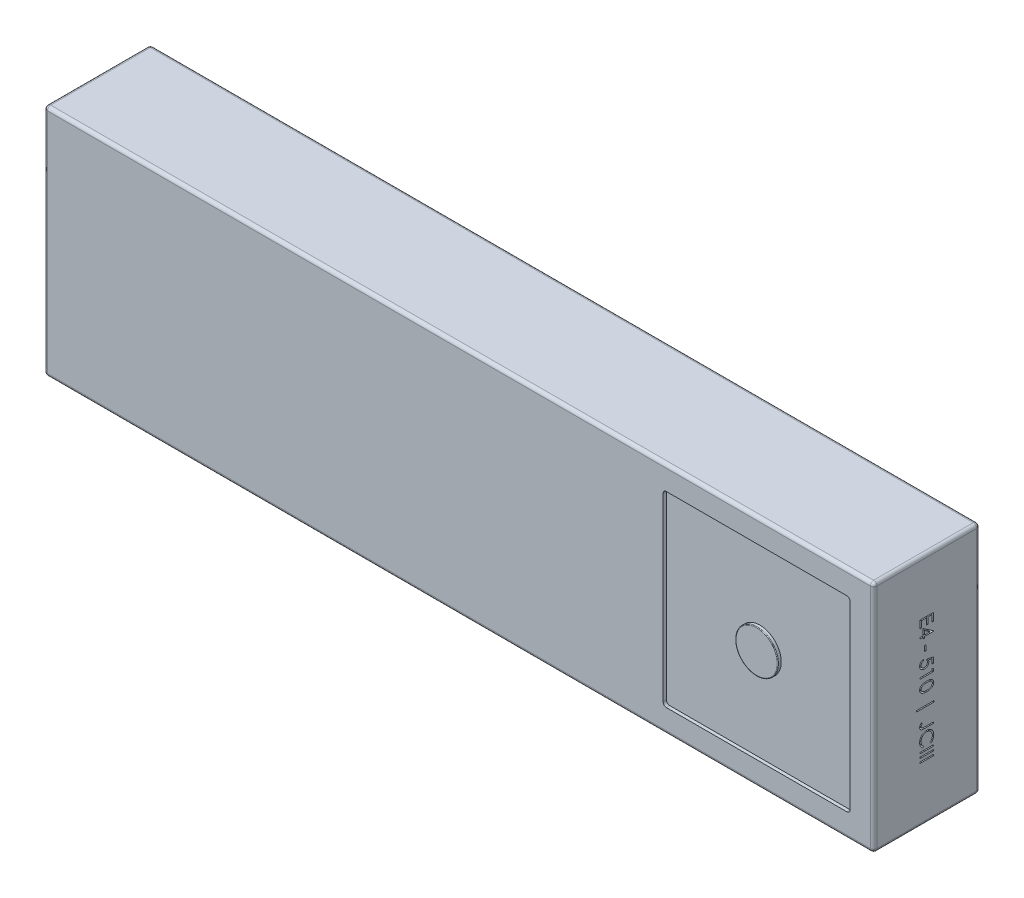
SolidWorks part; units mm, degrees
ref_plane "Front Plane" through (0, 0, 0) normal (0, 0, 1) x (1, 0, 0)
ref_plane "Top Plane" through (0, 0, 0) normal (0, 1, 0) x (1, 0, 0)
ref_plane "Right Plane" through (0, 0, 0) normal (1, 0, 0) x (0, 0, -1)
sketch "Sketch1" plane through (0, 0, 0) normal (0, 0, 1) x (1, 0, 0)
  line L1 (-61.9125, 17.4625) -> (61.9125, 17.4625)
  line L2 (-61.9125, 17.4625) -> (-61.9125, -17.4625)
  line L3 (-61.9125, -17.4625) -> (61.9125, -17.4625)
  line L4 (61.9125, 17.4625) -> (61.9125, -17.4625)
  line L5 (-61.9125, 17.4625) -> (61.9125, -17.4625) construction
  line L6 (-61.9125, -17.4625) -> (61.9125, 17.4625) construction
  point P0 (0, 0)
  dimension "D1" = 123.825
  dimension "D2" = 34.925
extrude "Boss-Extrude1" add sketch "Sketch1" along normal mid plane 15.875
fillet "Fillet1" radius 0.5 12 edges at (0, -17.4625, 7.9375) (-61.9125, 0, 7.9375) (0, 17.4625, 7.9375) (61.9125, 0, 7.9375) (61.9125, 0, -7.9375) (-61.9125, 0, -7.9375) (0, -17.4625, -7.9375) (61.9125, -17.4625, 0) (-61.9125, -17.4625, 0) (-61.9125, 17.4625, 0) (61.9125, 17.4625, 0) (0, 17.4625, -7.9375)
sketch "Sketch2" plane through (0, 0, 7.9375) normal (0, 0, 1) x (1, 0, 0)
  line L0 (0, 0) -> (61.9125, 0) construction
  line L1 (61.9125, 16.9625) -> (61.9125, -16.9625) construction
  line L2 (-61.4125, -16.9625) -> (61.4125, -16.9625) construction
  line L3 (30.4875, 13.9625) -> (58.4125, 13.9625)
  line L4 (30.4875, 13.9625) -> (30.4875, -13.9625)
  line L5 (30.4875, -13.9625) -> (58.4125, -13.9625)
  line L6 (58.4125, 13.9625) -> (58.4125, -13.9625)
  line L7 (30.4875, 13.9625) -> (58.4125, -13.9625) construction
  line L8 (30.4875, -13.9625) -> (58.4125, 13.9625) construction
  line L9 (61.4125, -16.9625) -> (61.4125, 16.9625) construction
  point P5 (44.45, 0)
  dimension "D1" = 3
  dimension "D2" = 3
extrude "Cut-Extrude1" cut sketch "Sketch2" against normal blind 0.5
sketch "Sketch3" plane through (0, 0, 7.4375) normal (0, 0, 1) x (1, 0, 0)
  line L0 (30.4875, 0) -> (58.4125, 0) construction
  line L1 (30.4875, 13.9625) -> (30.4875, -13.9625) construction
  line L2 (58.4125, -13.9625) -> (58.4125, 13.9625) construction
  line L3 (58.4125, 0) -> (44.45, 13.9625) construction
  line L4 (58.4125, 13.9625) -> (30.4875, 13.9625) construction
  line L5 (44.45, 13.9625) -> (44.45, 0) construction
  circle A0 centre (44.45, 0) radius 3.175
  dimension "D1" = 6.35
extrude "Boss-Extrude2" add sketch "Sketch3" along normal up to surface (0.5 mm away) up to face at (44.45, 0, 7.9375)
fillet "Fillet2" radius 0.5 4 edges at (58.4125, -13.9625, 7.6875) (30.4875, 13.9625, 7.6875) (58.4125, 13.9625, 7.6875) (30.4875, -13.9625, 7.6875)
fillet "Fillet3" radius 0.1 1 edges at (47.625, 0, 7.9375)
sketch "Sketch4" plane through (61.9125, 0, 0) normal (1, 0, 0) x (0, 0, -1)
  line L0 (-1.011, 16.9625) -> (-1.011, -16.9625) construction
  line L1 (7.4375, 16.9625) -> (-7.4375, 16.9625) construction
  line L2 (-7.4375, -16.9625) -> (7.4375, -16.9625) construction
  text T0 "E4 - 510 | JCIII" font "Century Gothic" height 2
extrude "Cut-Extrude2" cut sketch "Sketch4" against normal blind 1
equation "\"CamWidth\"= 4 + 14 / 16"
equation "\"CamHeight\"= 1 + 3 / 8"
equation "\"CamDepth\"= 5 / 8"
equation "\"D1@Sketch1\"=\"CamWidth\""
equation "\"D2@Sketch1\"=\"CamHeight\""
equation "\"D1@Boss-Extrude1\"=\"CamDepth\""
